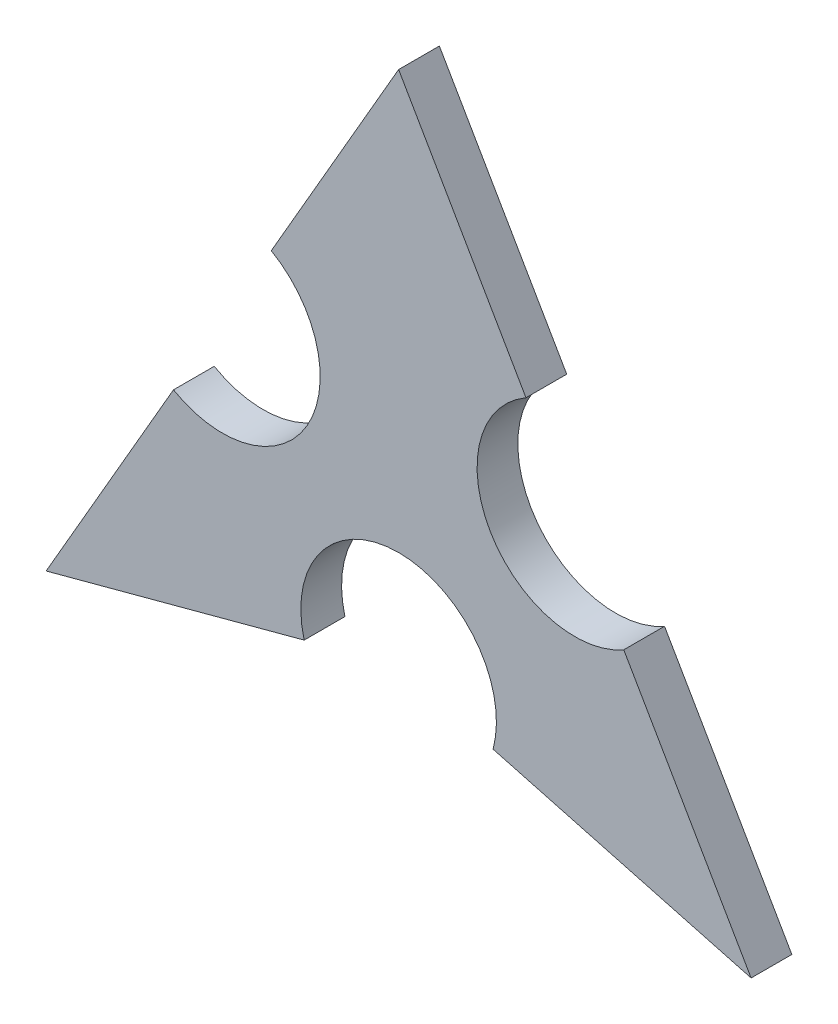
SolidWorks part; units mm, degrees
ref_plane "Front Plane" through (0, 0, 0) normal (0, 0, 1) x (1, 0, 0)
ref_plane "Top Plane" through (0, 0, 0) normal (0, 1, 0) x (1, 0, 0)
ref_plane "Right Plane" through (0, 0, 0) normal (1, 0, 0) x (0, 0, -1)
sketch "Sketch1" plane through (0, 0, 0) normal (0, 0, 1) x (1, 0, 0)
  line L0 (0, 0) -> (0, 89720.2147) construction
  line L1 (0, 0) -> (89720.2147, 0) construction
  line L2 (0, 74.9112) -> (-31.25, 20.7846)
  line L3 (-86.5, -74.9112) -> (-23.1822, -57.9452)
  line L4 (0, -51.7336) -> (0, 74.9112)
  line L5 (86.5, -74.9112) -> (23.1822, -57.9452)
  line L6 (0, 74.9112) -> (31.25, 20.7846)
  line L7 (-55.25, -20.7846) -> (-86.5, -74.9112)
  line L8 (55.25, -20.7846) -> (86.5, -74.9112)
  line L9 (-55.25, -20.7846) -> (-31.25, 20.7846) construction
  line L10 (-23.1822, -57.9452) -> (17.3509, -47.0844) construction
  arc A0 (-55.25, -20.7846) -> (-31.25, 20.7846) centre (-43.25, 0) ccw
  arc A1 (23.1822, -57.9452) -> (-23.1822, -57.9452) centre (0, -51.7336) ccw
  arc A2 (55.25, -20.7846) -> (31.25, 20.7846) centre (43.25, 0) cw
  point P10 (-1.9869, -47.0844)
  dimension "D1" = 86.5
  dimension "D2" = 48
  dimension "D4" = 173
  dimension "D6" = 48
  dimension "D3" = 86.5
  dimension "D5" = 45
  dimension "D7" = 45
extrude "Boss-Extrude1" add sketch "Sketch1" along normal mid plane 10 contours L8 A2 L6 L4 A1 L5 | A1 L4 L2 A0 L7 L3
